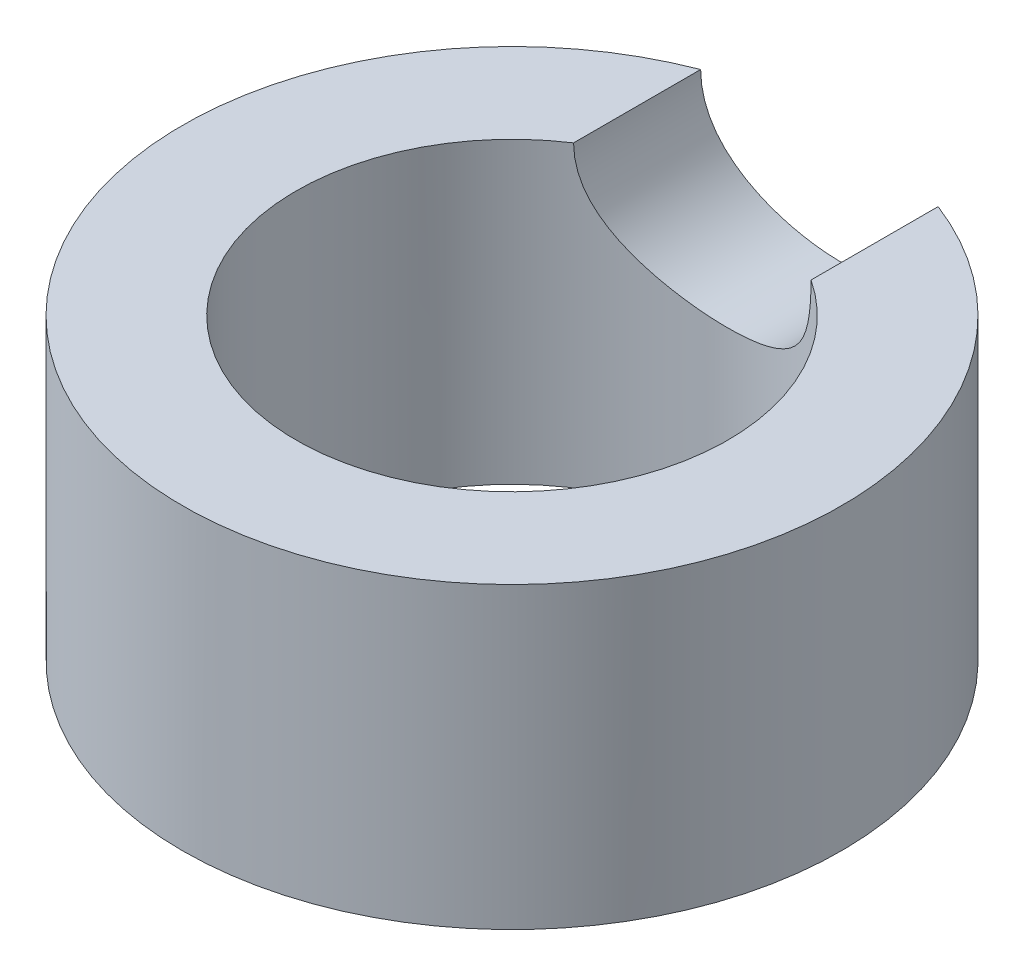
SolidWorks part; units mm, degrees
ref_plane "Front Plane" through (0, 0, 0) normal (0, 0, 1) x (1, 0, 0)
ref_plane "Top Plane" through (0, 0, 0) normal (0, 1, 0) x (1, 0, 0)
ref_plane "Right Plane" through (0, 0, 0) normal (1, 0, 0) x (0, 0, -1)
sketch "Sketch1" plane through (0, 0, 0) normal (0, 1, 0) x (1, 0, 0)
  circle A0 centre (0, 0) radius 29
  circle A1 centre (0, 0) radius 19
  dimension "D1" = 58
  dimension "D2" = 10
extrude "Boss-Extrude1" add sketch "Sketch1" along normal blind 26.3
sketch "Sketch2" plane through (0, 0, 0) normal (0, 0, 1) x (1, 0, 0)
  line L0 (29, 26.3) -> (-29, 26.3) construction
  circle A0 centre (0, 26.3) radius 10.45
  dimension "D1" = 20.9
extrude "Cut-Extrude1" cut sketch "Sketch2" against normal through all
